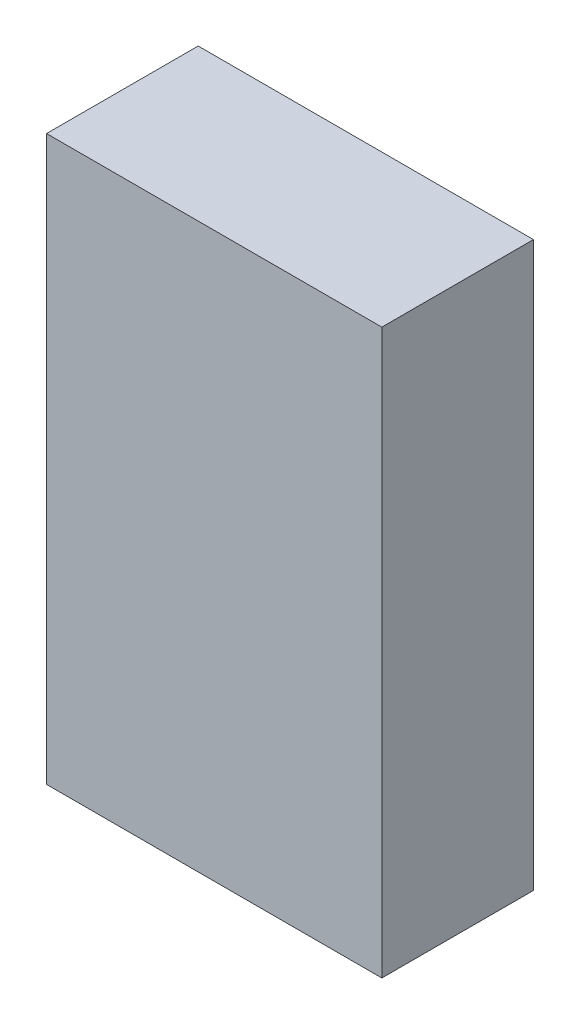
SolidWorks part; units mm, degrees
ref_plane "Front Plane" through (0, 0, 0) normal (0, 0, 1) x (1, 0, 0)
ref_plane "Top Plane" through (0, 0, 0) normal (0, 1, 0) x (1, 0, 0)
ref_plane "Right Plane" through (0, 0, 0) normal (1, 0, 0) x (0, 0, -1)
sketch "Sketch1" plane through (0, 0, 0) normal (0, 0, 1) x (1, 0, 0)
  line L1 (-17.25, -29) -> (17.25, -29)
  line L2 (-17.25, -29) -> (-17.25, 29)
  line L3 (-17.25, 29) -> (17.25, 29)
  line L4 (17.25, -29) -> (17.25, 29)
  line L5 (-17.25, -29) -> (17.25, 29) construction
  line L6 (-17.25, 29) -> (17.25, -29) construction
extrude "Envelope" add sketch "Sketch1" along normal blind 15.6
